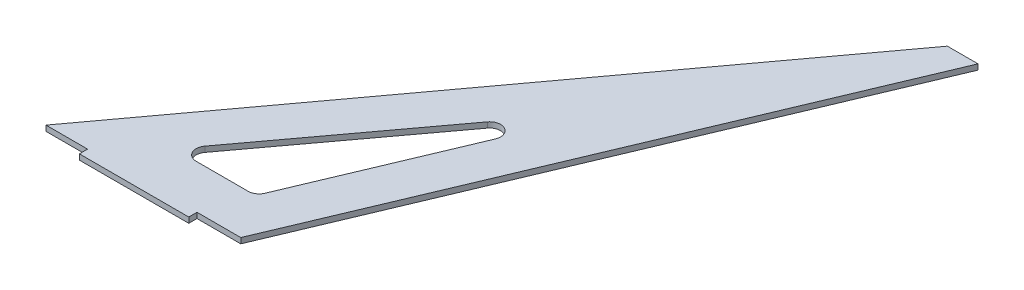
SolidWorks part; units mm, degrees
material "Balsa"
ref_plane "Front Plane" through (0, 0, 0) normal (0, 0, 1) x (1, 0, 0)
ref_plane "Top Plane" through (0, 0, 0) normal (0, 1, 0) x (1, 0, 0)
ref_plane "Right Plane" through (0, 0, 0) normal (1, 0, 0) x (0, 0, -1)
sketch "Sketch1" plane through (0, 0, 0) normal (0, 1, 0) x (1, 0, 0)
  line L0 (0, 0) -> (160.7625, 0) construction
  line L1 (0, 0) -> (0, -107.2466) construction
  line L2 (0, 301.244) -> (-17.78, 301.244)
  line L3 (-17.78, 301.244) -> (-240.9313, 0)
  line L4 (-240.9313, 0) -> (-126.6313, 0)
  line L5 (-126.6313, 0) -> (0, 301.244)
  dimension "D1" = 17.78
  dimension "D2" = 301.244
  dimension "D3" = 67.2
  dimension "D4" = 114.3
extrude "Boss-Extrude1" add sketch "Sketch1" along normal blind 3.175
sketch "Sketch2" plane through (0, 3.175, 0) normal (0, 1, 0) x (1, 0, 0)
  line L8 (-143.507, 25.4) -> (-81.8458, 172.0863)
  line L9 (-81.8458, 172.0863) -> (-190.506, 25.4)
  line L10 (-190.506, 25.4) -> (-143.507, 25.4)
  line L11 (-143.507, 25.4) -> (-81.8458, 172.0863)
  line L12 (-81.8458, 172.0863) -> (-190.506, 25.4)
  line L13 (-190.506, 25.4) -> (-143.507, 25.4)
  dimension "D1" = 25.4
extrude "Cut-Extrude1" cut sketch "Sketch2" against normal blind 3.175
fillet "Fillet1" radius 6.35 3 edges at (-81.8458, 1.5875, -172.0863) (-143.507, 1.5875, -25.4) (-190.506, 1.5875, -25.4)
sketch "Sketch3" plane through (0, 0, 0) normal (0, 0, 1) x (1, 0, 0)
  line L0 (-183.7813, 3.175) -> (-183.7813, 0) construction
  line L1 (-240.9313, 3.175) -> (-126.6313, 3.175) construction
  line L2 (-240.9313, 0) -> (-126.6313, 0) construction
  line L4 (-215.5313, 3.175) -> (-152.0313, 3.175)
  line L5 (-215.5313, 3.175) -> (-215.5313, 0)
  line L6 (-215.5313, 0) -> (-152.0313, 0)
  line L7 (-152.0313, 3.175) -> (-152.0313, 0)
  line L8 (-215.5313, 3.175) -> (-152.0313, 0) construction
  line L9 (-215.5313, 0) -> (-152.0313, 3.175) construction
  point P6 (-183.7813, 1.5875)
  dimension "D1" = 63.5
extrude "Boss-Extrude2" add sketch "Sketch3" along normal blind 4.7625
sketch "Sketch4" plane through (0, 3.175, 0) normal (0, 1, 0) x (1, 0, 0)
  line L0 (-17.78, 301.244) -> (-239.6613, 0)
  line L1 (-240.9313, 0) -> (-215.5313, 0) construction
  line L2 (-239.6613, 0) -> (-240.9313, 0)
  line L3 (-240.9313, 0) -> (-17.78, 301.244)
  dimension "D1" = 1.27
extrude "Cut-Extrude2" cut sketch "Sketch4" against normal through all
